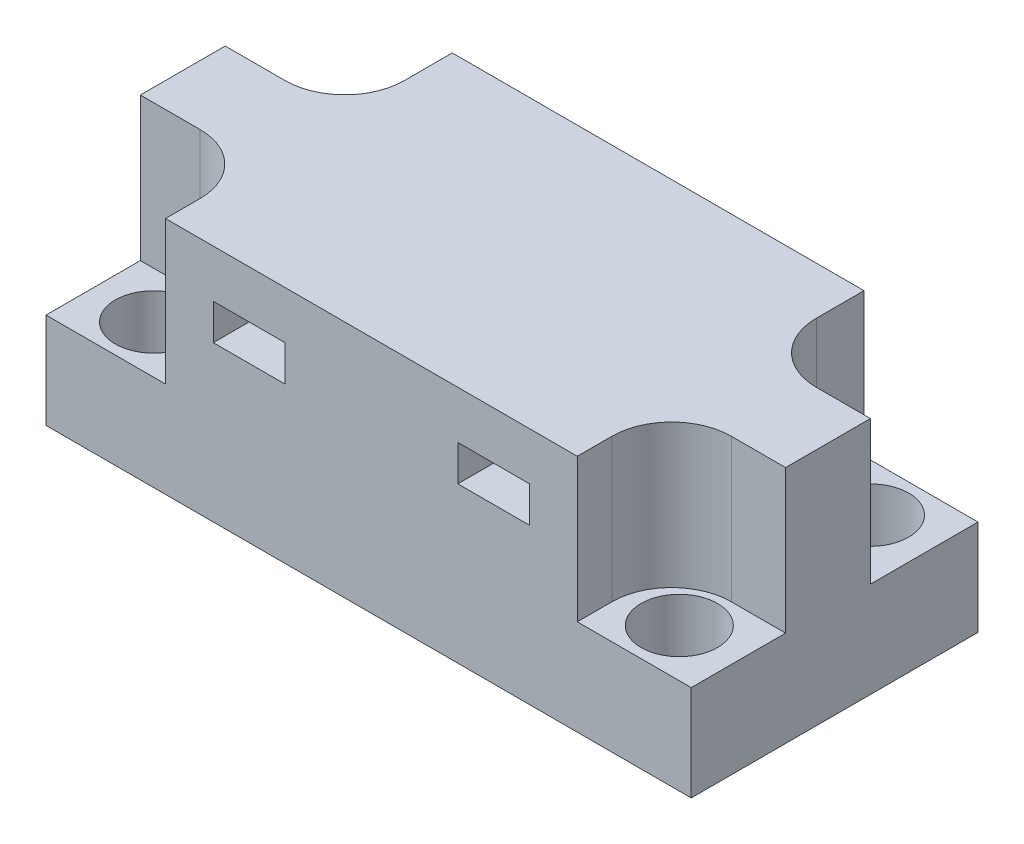
SolidWorks part; units mm, degrees
ref_plane "前基準面" through (0, 0, 0) normal (0, 0, 1) x (1, 0, 0)
ref_plane "上基準面" through (0, 0, 0) normal (0, 1, 0) x (1, 0, 0)
ref_plane "右基準面" through (0, 0, 0) normal (1, 0, 0) x (0, 0, -1)
sketch "草圖1" plane through (0, 0, 0) normal (0, 1, 0) x (1, 0, 0)
  line L1 (-13500, 6000) -> (13500, 6000)
  line L2 (-13500, 6000) -> (-13500, -6000)
  line L3 (-13500, -6000) -> (13500, -6000)
  line L4 (13500, 6000) -> (13500, -6000)
  line L5 (-13500, 6000) -> (13500, -6000) construction
  line L6 (-13500, -6000) -> (13500, 6000) construction
  line L7 (-11000, 4000) -> (11000, 4000) construction
  line L8 (-11000, 4000) -> (-11000, -4000) construction
  line L9 (-11000, -4000) -> (11000, -4000) construction
  line L10 (11000, 4000) -> (11000, -4000) construction
  line L11 (-11000, 4000) -> (11000, -4000) construction
  line L12 (-11000, -4000) -> (11000, 4000) construction
  circle A0 centre (-11000, 4000) radius 1600
  circle A1 centre (11000, 4000) radius 1600
  circle A2 centre (-11000, -4000) radius 1600
  circle A3 centre (11000, -4000) radius 1600
  point P0 (0, 0)
  point P6 (0, 0)
  dimension "D5" = 3200
  dimension "D1" = 12000
  dimension "D2" = 27000
  dimension "D3" = 8000
  dimension "D4" = 22000
extrude "填料-伸長1" add sketch "草圖1" along normal blind 10000
sketch "草圖2" plane through (13500, 0, 0) normal (1, 0, 0) x (0, 0, -1)
  line L0 (-6000, 0) -> (6000, 0) construction
  line L1 (-6000, 10000) -> (-2000, 10000)
  line L2 (-6000, 10000) -> (-6000, 3000)
  line L3 (-6000, 3000) -> (-2000, 3000)
  line L4 (-2000, 10000) -> (-2000, 3000)
  line L5 (6000, 10000) -> (2000, 10000)
  line L6 (6000, 10000) -> (6000, 3000)
  line L7 (6000, 3000) -> (2000, 3000)
  line L8 (2000, 10000) -> (2000, 3000)
  dimension "D1" = 4000
  dimension "D2" = 4000
  dimension "D3" = 3000
sketch "草圖3" plane through (0, 10000, 0) normal (0, 1, 0) x (1, 0, 0)
  line L0 (-11000, 6500) -> (-13500, 6500)
  line L1 (-13500, 6500) -> (-13500, 4000)
  line L2 (115.8975, 6000) -> (115.8975, -6552.1176) construction
  line L3 (13500, 6000) -> (-13500, 6000) construction
  line L4 (115.8975, -6552.1176) -> (-9837.7929, -276.0588) construction
  line L5 (-9837.7929, -276.0588) -> (9589.9707, -276.0588) construction
  line L6 (-8500, 4000) -> (-8500, 6500)
  line L7 (-8500, 6500) -> (-11000, 6500)
  line L8 (-13500, 4000) -> (-13500, 1500)
  line L9 (-13500, 6000) -> (-13500, -6000) construction
  line L10 (-13500, 1500) -> (-11000, 1500)
  line L11 (13731.795, 1500) -> (11231.795, 1500)
  line L12 (13731.795, 4000) -> (13731.795, 1500)
  line L13 (8731.795, 6500) -> (11231.795, 6500)
  line L14 (8731.795, 4000) -> (8731.795, 6500)
  line L15 (13731.795, 6500) -> (13731.795, 4000)
  line L16 (11231.795, 6500) -> (13731.795, 6500)
  line L17 (11231.795, -7052.1176) -> (13731.795, -7052.1176)
  line L18 (13731.795, -7052.1176) -> (13731.795, -4552.1176)
  line L19 (8731.795, -4552.1176) -> (8731.795, -7052.1176)
  line L20 (8731.795, -7052.1176) -> (11231.795, -7052.1176)
  line L21 (13731.795, -4552.1176) -> (13731.795, -2052.1176)
  line L22 (13731.795, -2052.1176) -> (11231.795, -2052.1176)
  line L23 (-13500, -2052.1176) -> (-11000, -2052.1176)
  line L24 (-13500, -4552.1176) -> (-13500, -2052.1176)
  line L25 (-8500, -7052.1176) -> (-11000, -7052.1176)
  line L26 (-8500, -4552.1176) -> (-8500, -7052.1176)
  line L27 (-13500, -7052.1176) -> (-13500, -4552.1176)
  line L28 (-11000, -7052.1176) -> (-13500, -7052.1176)
  arc A0 (-11000, 1500) -> (-8500, 4000) centre (-11000, 4000) ccw
  arc A1 (11231.795, 1500) -> (8731.795, 4000) centre (11231.795, 4000) cw
  arc A2 (11231.795, -2052.1176) -> (8731.795, -4552.1176) centre (11231.795, -4552.1176) ccw
  arc A3 (-11000, -2052.1176) -> (-8500, -4552.1176) centre (-11000, -4552.1176) cw
  dimension "D1" = 5000
extrude "除料-伸長3" cut sketch "草圖3" against normal blind 6000
sketch "草圖4" plane through (0, 0, 2052.1176) normal (0, 0, 1) x (1, 0, 0)
  line L0 (13500, 10000) -> (13500, 3000) construction
  line L1 (11500, 8000) -> (9000, 8000)
  line L2 (11500, 8000) -> (11500, 6500)
  line L3 (11500, 6500) -> (9000, 6500)
  line L4 (9000, 8000) -> (9000, 6500)
  line L5 (11231.795, 10000) -> (8731.795, 10000) construction
  line L6 (115.8975, 10000) -> (115.8975, -927.0873) construction
  line L7 (-8500, 10000) -> (8731.795, 10000) construction
  line L8 (-8768.205, 8000) -> (-8768.205, 6500)
  line L9 (-11268.205, 6500) -> (-8768.205, 6500)
  line L10 (-11268.205, 8000) -> (-11268.205, 6500)
  line L11 (-11268.205, 8000) -> (-8768.205, 8000)
  dimension "D1" = 2500
  dimension "D2" = 1500
  dimension "D3" = 2000
  dimension "D4" = 2000
sketch "草圖5" plane through (0, 0, 6000) normal (0, 0, 1) x (1, 0, 0)
  line L0 (-8500, 10000) -> (8731.795, 10000) construction
  line L1 (-6500, 8000) -> (-3500, 8000)
  line L2 (-6500, 8000) -> (-6500, 6500)
  line L3 (-6500, 6500) -> (-3500, 6500)
  line L4 (-3500, 8000) -> (-3500, 6500)
  line L5 (-8500, 4000) -> (-8500, 10000) construction
  line L6 (115.8975, 10000) -> (115.8975, 3846.9051) construction
  line L7 (115.8975, 10000) -> (115.8975, -927.0873) construction
  line L8 (3731.795, 8000) -> (3731.795, 6500)
  line L9 (6731.795, 6500) -> (3731.795, 6500)
  line L10 (6731.795, 8000) -> (6731.795, 6500)
  line L11 (6731.795, 8000) -> (3731.795, 8000)
  dimension "D1" = 3000
  dimension "D2" = 1500
  dimension "D3" = 2000
  dimension "D4" = 2000
extrude "除料-伸長4" cut sketch "草圖5" against normal through all
